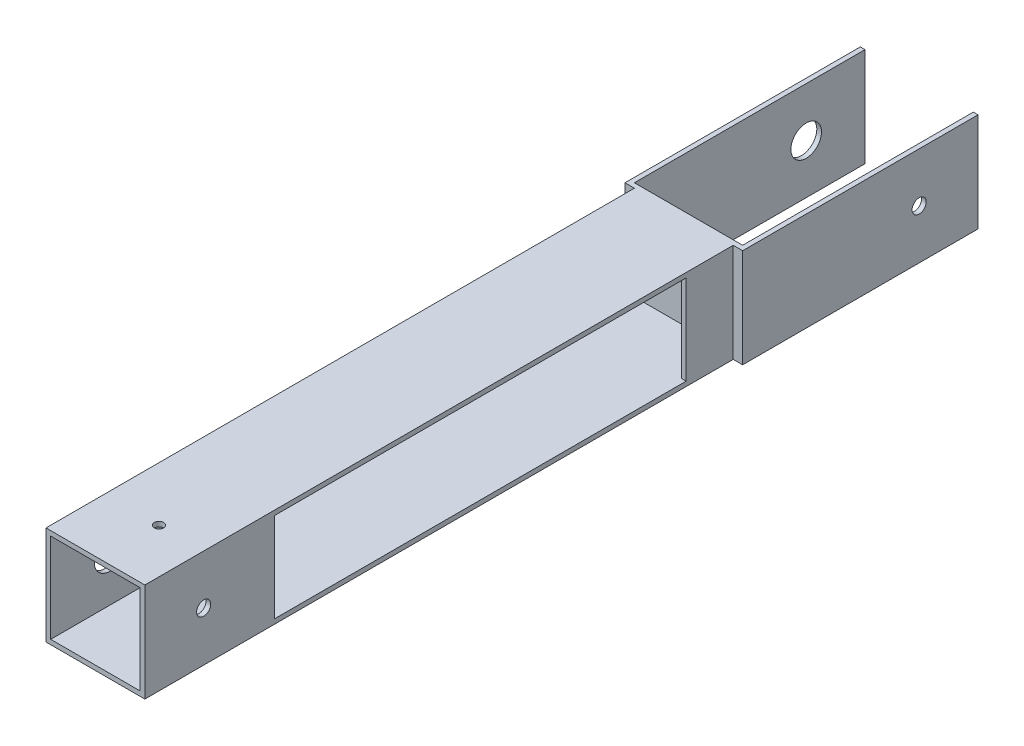
SolidWorks part; units mm, degrees
material "6061 Alloy"
ref_plane "Front Plane" through (0, 0, 0) normal (0, 0, 1) x (1, 0, 0)
ref_plane "Top Plane" through (0, 0, 0) normal (0, 1, 0) x (1, 0, 0)
ref_plane "Right Plane" through (0, 0, 0) normal (1, 0, 0) x (0, 0, -1)
sketch "Sketch1" plane through (0, 0, 0) normal (0, 0, 1) x (1, 0, 0)
  line L1 (-21, -21) -> (21, -21)
  line L2 (-21, -21) -> (-21, 21)
  line L3 (-21, 21) -> (21, 21)
  line L4 (21, -21) -> (21, 21)
  line L5 (-21, -21) -> (21, 21) construction
  line L6 (-21, 21) -> (21, -21) construction
  line L7 (-19, -19) -> (19, -19)
  line L8 (-19, -19) -> (-19, 19)
  line L9 (-19, 19) -> (19, 19)
  line L10 (19, -19) -> (19, 19)
  line L11 (-19, -19) -> (19, 19) construction
  line L12 (-19, 19) -> (19, -19) construction
  point P0 (0, 0)
  point P6 (0, 0)
  dimension "D1" = 42
  dimension "D2" = 2
  dimension "D3" = 2
extrude "Boss-Extrude1" add sketch "Sketch1" against normal blind 250
sketch "Sketch2" plane through (0, 0, 0) normal (0, 1, 0) x (1, 0, 0)
  line L0 (21, 250) -> (-21, 250) construction
  line L1 (-25, 250) -> (-25, 350)
  line L2 (-25, 350) -> (-23, 350)
  line L3 (-23, 350) -> (-23, 252)
  line L4 (-23, 252) -> (23, 252)
  line L5 (23, 252) -> (23, 350)
  line L6 (23, 350) -> (25, 350)
  line L7 (25, 350) -> (25, 250)
  line L8 (25, 250) -> (-25, 250)
  line L9 (0, 250) -> (0, 252.2106) construction
  dimension "D1" = 46
  dimension "D2" = 2
  dimension "D3" = 2
  dimension "D4" = 2
  dimension "D5" = 100
extrude "Boss-Extrude2" add sketch "Sketch2" along normal mid plane 42
sketch "Sketch3" plane through (-25, 0, 0) normal (-1, 0, 0) x (0, 0, 1)
  line L0 (0, 21) -> (0, -21) construction
  line L2 (-350, 21) -> (-350, -21) construction
  line L3 (-350, 21) -> (-250, 21) construction
  circle A0 centre (-25, 0) radius 6.5
  circle A1 centre (-325, 0) radius 6.5
  dimension "D1" = 13
  dimension "D3" = 13
  dimension "D2" = 25
  dimension "D4" = 25
  dimension "D5" = 21
extrude "Cut-Extrude1" cut sketch "Sketch3" against normal up to next
sketch "Sketch4" plane through (25, 0, 0) normal (1, 0, 0) x (0, 0, -1)
  circle A0 centre (325, 0) radius 6.5 construction
  circle A1 centre (325, 0) radius 6.5 construction
  circle A3 centre (325, 0) radius 3
  circle A4 centre (25, 0) radius 6.5 construction
  circle A5 centre (25, 0) radius 6.5 construction
  circle A6 centre (25, 0) radius 3
  dimension "D1" = 6
  dimension "D2" = 6
extrude "Cut-Extrude2" cut sketch "Sketch4" against normal up to next
sketch "Sketch5" plane through (21, 0, 0) normal (1, 0, 0) x (0, 0, -1)
  line L0 (250, 21) -> (0, 21) construction
  line L1 (230, -19) -> (55, -19)
  line L2 (230, -19) -> (230, 19)
  line L3 (230, 19) -> (55, 19)
  line L4 (55, -19) -> (55, 19)
  line L5 (230, -19) -> (55, 19) construction
  line L6 (230, 19) -> (55, -19) construction
  line L7 (250, -21) -> (0, -21) construction
  line L8 (0, -21) -> (0, 21) construction
  point P0 (142.5, 0)
  dimension "D1" = 2
  dimension "D2" = 2
  dimension "D3" = 55
  dimension "D4" = 175
extrude "Cut-Extrude3" cut sketch "Sketch5" against normal blind 10
sketch "Sketch6" plane through (0, 21, 0) normal (0, 1, 0) x (1, 0, 0)
  line L0 (21, 0) -> (-21, 0) construction
  line L1 (21, 250) -> (21, 0) construction
  circle A0 centre (2, 25) radius 2
  point P4 (0, 0)
  dimension "D2" = 4
  dimension "D1" = 25
  dimension "D3" = 19
extrude "Cut-Extrude4" cut sketch "Sketch6" against normal through all
